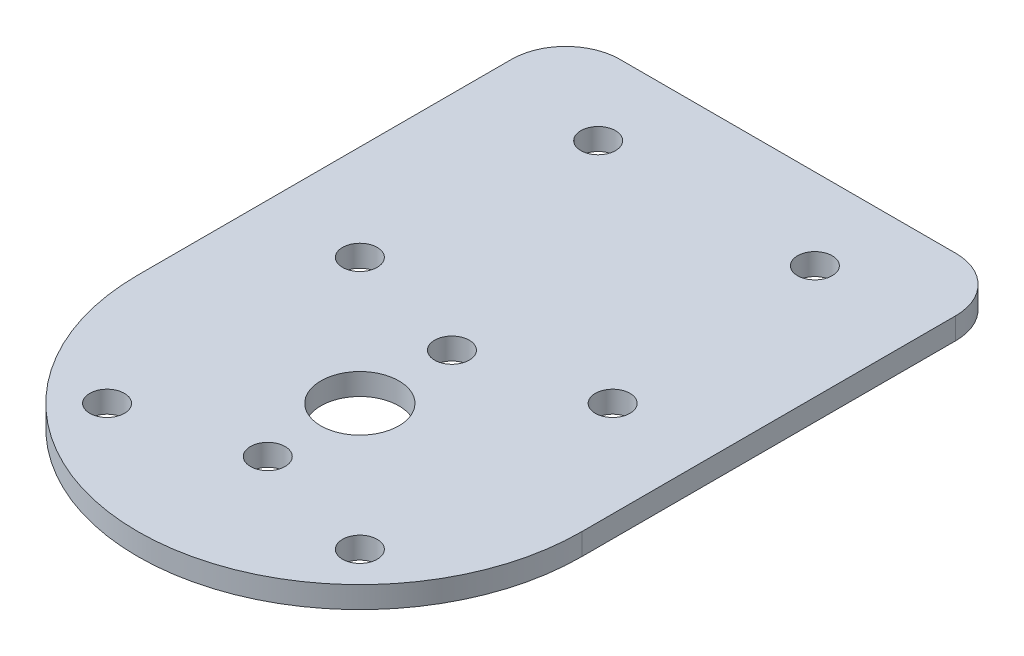
SolidWorks part; units mm, degrees
material "Carbon Fiber"
ref_plane "前视基准面" through (0, 0, 0) normal (0, 0, 1) x (1, 0, 0)
ref_plane "上视基准面" through (0, 0, 0) normal (0, 1, 0) x (1, 0, 0)
ref_plane "右视基准面" through (0, 0, 0) normal (1, 0, 0) x (0, 0, -1)
sketch "草图1" plane through (0, 0, 0) normal (0, 1, 0) x (1, 0, 0)
  line L0 (0, 0) -> (-8.8388, -8.8388) construction
  line L1 (-20.5, 0) -> (-20.5, 39.5)
  line L2 (20.5, 0) -> (20.5, 39.5)
  line L3 (20.5, 39.5) -> (-20.5, 39.5)
  line L4 (0, 39.5) -> (0, 24.5) construction
  line L5 (-20.5, 32) -> (-10, 32) construction
  line L6 (-10, 32) -> (10, 32) construction
  line L7 (10, 32) -> (20.5, 32) construction
  line L8 (0, 8.5) -> (0, -8.5) construction
  line L9 (0, 24.5) -> (0, 20.5) construction
  circle A0 centre (0, 0) radius 3.6
  circle A1 centre (0, 0) radius 12.5
  circle A2 centre (0, 0) radius 20.5
  circle A3 centre (-11.6673, -11.6673) radius 1.6
  circle A4 centre (-10, 32) radius 1.6
  circle A5 centre (10, 32) radius 1.6
  circle A6 centre (-11.6673, 11.6673) radius 1.6
  circle A7 centre (11.6673, 11.6673) radius 1.6
  circle A8 centre (11.6673, -11.6673) radius 1.6
  circle A9 centre (0, 8.5) radius 1.6
  circle A10 centre (0, -8.5) radius 1.6
  circle A11 centre (0, 0) radius 16.5 construction
  point P17 (0, 32)
  point P31 (0, 0)
  dimension "D1" = 7.2
  dimension "D2" = 25
  dimension "D4" = 3.2
  dimension "D7" = 3.2
  dimension "D3" = 33
  dimension "D11" = 41
  dimension "D5" = 20
  dimension "D6" = 15
  dimension "D9" = 17
  dimension "D10" = 45
  dimension "D12" = 4
  dimension "D8" = 4
extrude "凸台-拉伸1" add sketch "草图1" along normal blind 2 contours A2 L2 L3 L1 A5 A4 | A2 A8 A7 A6 A3 A1 | A1 A10 A9 A0
fillet "圆角1" radius 5 2 edges at (20.5, 1, -39.5) (-20.5, 1, -39.5)
